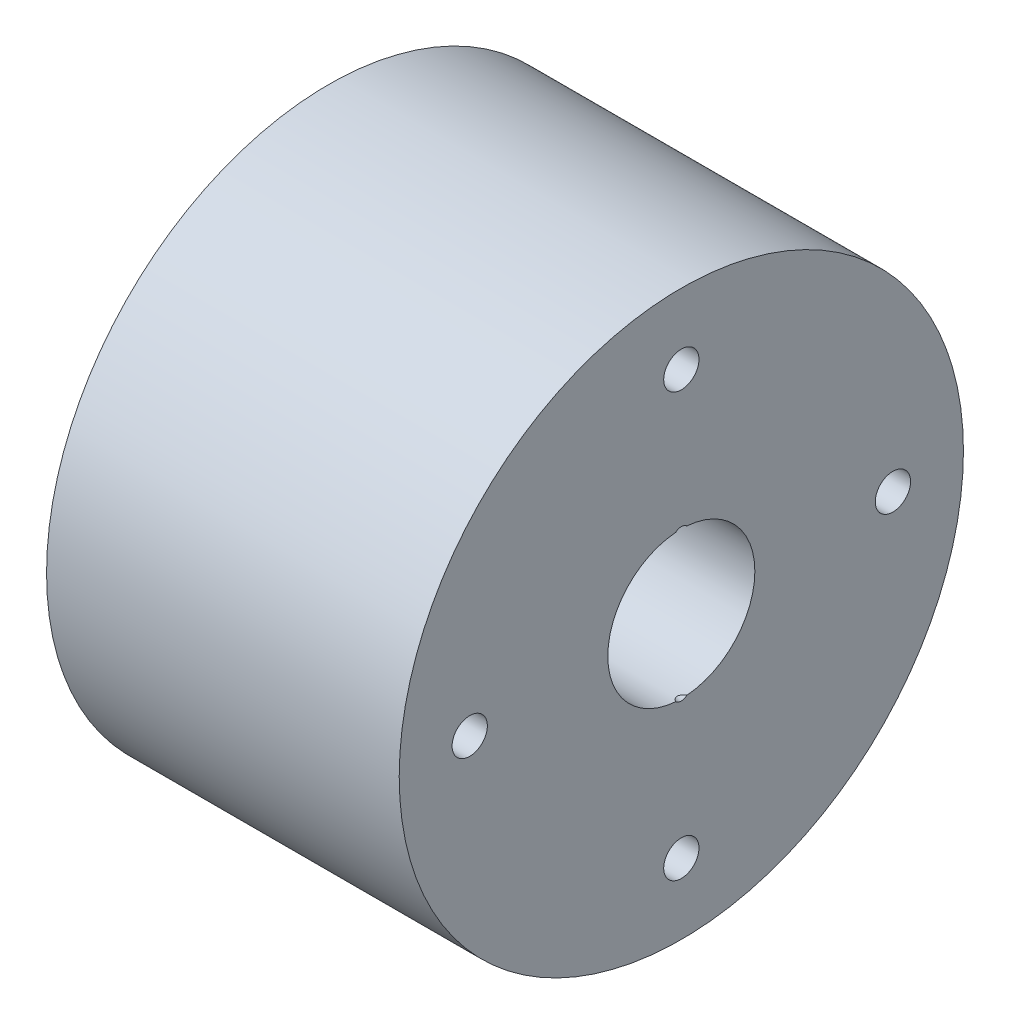
SolidWorks part; units mm, degrees
ref_plane "Front Plane" through (0, 0, 0) normal (0, 0, 1) x (1, 0, 0)
ref_plane "Top Plane" through (0, 0, 0) normal (0, 1, 0) x (1, 0, 0)
ref_plane "Right Plane" through (0, 0, 0) normal (1, 0, 0) x (0, 0, -1)
sketch "Sketch1" plane through (0, 0, 0) normal (1, 0, 0) x (0, 0, -1)
  circle A0 centre (0, 0) radius 40
  dimension "D1" = 80
extrude "Boss-Extrude1" add sketch "Sketch1" along normal blind 50
sketch "Sketch2" plane through (50, 0, 0) normal (1, 0, 0) x (0, 0, -1)
  circle A0 centre (0, 0) radius 10.425
  dimension "D1" = 20.85
extrude "Cut-Extrude1" cut sketch "Sketch2" against normal blind 30
sketch "Sketch3" plane through (0, 0, 0) normal (-1, 0, 0) x (0, 0, 1)
  circle A0 centre (0, 0) radius 20
  circle A1 centre (0, 0) radius 10
  dimension "D1" = 40
  dimension "D2" = 20
extrude "Cut-Extrude2" cut sketch "Sketch3" against normal blind 5
sketch "Sketch4" plane through (0, 0, 0) normal (-1, 0, 0) x (0, 0, 1)
  circle A0 centre (0, 0) radius 0.5
  dimension "D1" = 1
extrude "Cut-Extrude3" cut sketch "Sketch4" against normal through all
sketch "Sketch5" plane through (0, 0, 0) normal (-1, 0, 0) x (0, 0, 1)
  circle A0 centre (0, 0) radius 30 construction
  circle A1 centre (0, 30) radius 2.5
  circle A2 centre (30, 0) radius 2.5
  circle A3 centre (0, -30) radius 2.5
  circle A4 centre (-30, 0) radius 2.5
  point P14 (0, 0)
  dimension "D1" = 5
  dimension "D2" = 4
extrude "Cut-Extrude4" cut sketch "Sketch5" against normal through all
sketch "Sketch6" plane through (0, 0, 0) normal (0, 0, 1) x (1, 0, 0)
  line L0 (-60.0242, 0) -> (54.9833, 0) construction
  line L1 (0, 13.9892) -> (30, 0) construction
  line L2 (0, 20) -> (0, -20) construction
  line L3 (30, 0) -> (0, -13.9892) construction
  point P4 (-2.5204, 0)
  point P8 (0, 0)
  dimension "D1" = 25
  dimension "D2" = 25
  dimension "D3" = 30
  dimension "D4" = 33.1013
sketch3d "3DSketch2"
  line L0 (0, 13.9892, 0) -> (30, 0, 0) construction
sketch "Sketch7" plane through (0, 0, 0) normal (-0.9063, 0.4226, 0) x (0, 0, 1)
  line L0 (0, 12.6785) -> (0, -12.6785) construction
  line L1 (0, -25.3673) -> (0, 23.237) construction
  circle A0 centre (0, 12.6785) radius 1.25
  dimension "D1" = 2.5
extrude "Cut-Extrude5" cut sketch "Sketch7" against normal up to next and the other way up to next
mirror "Mirror1" about plane through (0, 0, 0) normal (0, 1, 0) of "Cut-Extrude5" second plane through (0, 0, 0) second plane normal (0, 0, 1)
